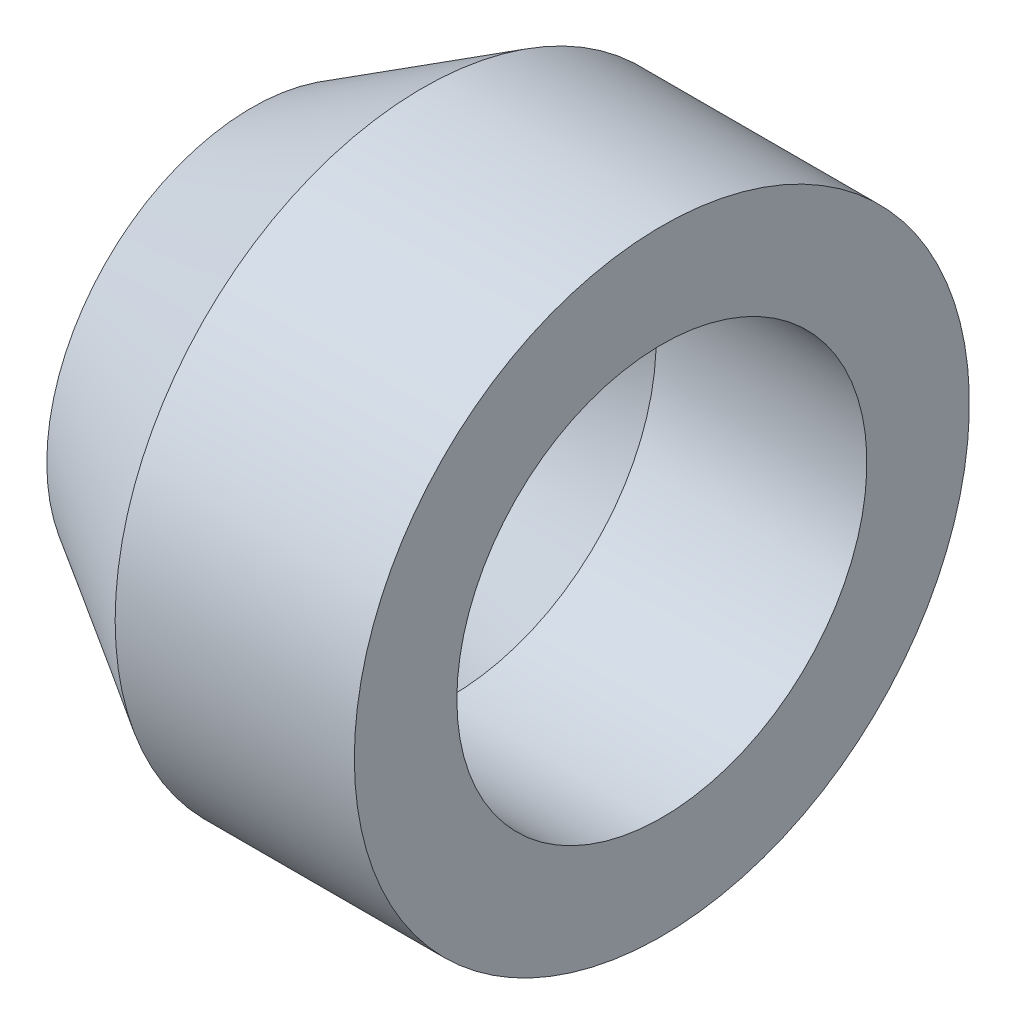
SolidWorks part; units mm, degrees
ref_plane "前视基准面" through (0, 0, 0) normal (0, 0, 1) x (1, 0, 0)
ref_plane "上视基准面" through (0, 0, 0) normal (0, 1, 0) x (1, 0, 0)
ref_plane "右视基准面" through (0, 0, 0) normal (1, 0, 0) x (0, 0, -1)
sketch "草图1" plane through (0, 0, 0) normal (0, 0, 1) x (1, 0, 0)
  line L1 (0, 6) -> (0, 9)
  line L2 (0, 9) -> (-7, 9)
  line L3 (-7, 9) -> (-12, 6)
  line L4 (-6.169, 6) -> (0, 6)
  line L5 (-12, 6) -> (-12, 0)
  line L6 (-27.6912, 0) -> (0, 0) construction
  line L7 (-12, 0) -> (-9, 0)
  line L8 (-6.169, 6) -> (-9, 4.3014)
  line L9 (-9, 4.3014) -> (-9, 0)
  line L10 (-3, 0) -> (-3, 6) construction
  line L11 (0, 0) -> (0, 9) construction
  line L12 (-3, 6) -> (-6.169, 6) construction
  line L13 (-9, 0) -> (-9.6239, 0)
  dimension "D1" = 9
  dimension "D2" = 7
  dimension "D4" = 6
  dimension "D5" = 3
revolve "旋转1" add sketch "草图1" angle 360 about L6
